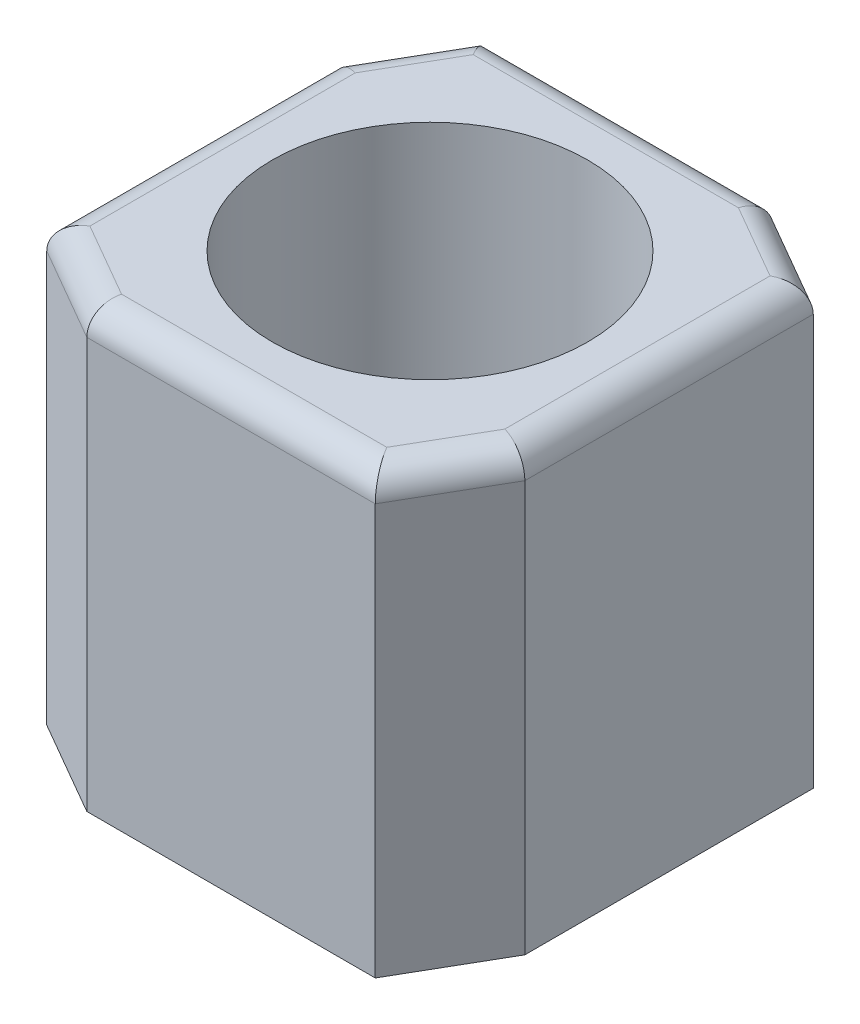
SolidWorks part; units mm, degrees
ref_plane "Front Plane" through (0, 0, 0) normal (0, 0, 1) x (1, 0, 0)
ref_plane "Top Plane" through (0, 0, 0) normal (0, 1, 0) x (1, 0, 0)
ref_plane "Right Plane" through (0, 0, 0) normal (1, 0, 0) x (0, 0, -1)
sketch "Sketch1" plane through (0, 0, 0) normal (0, 1, 0) x (1, 0, 0)
  line L1 (-3.175, -3.175) -> (3.175, -3.175)
  line L2 (-3.175, -3.175) -> (-3.175, 3.175)
  line L3 (-3.175, 3.175) -> (3.175, 3.175)
  line L4 (3.175, -3.175) -> (3.175, 3.175)
  line L5 (-3.175, -3.175) -> (3.175, 3.175) construction
  line L6 (-3.175, 3.175) -> (3.175, -3.175) construction
  circle A0 centre (0, 0) radius 2.286
  point P0 (0, 0)
  dimension "D1" = 4.572
  dimension "D2" = 6.35
  dimension "D3" = 6.35
extrude "Boss-Extrude1" add sketch "Sketch1" along normal blind 6.35
chamfer "Chamfer1" distance 0.7937 angle 60 4 edges at (-3.175, 3.175, -3.175) (3.175, 3.175, -3.175) (3.175, 3.175, 3.175) (-3.175, 3.175, 3.175)
fillet "Fillet1" radius 0.3969 8 edges at (3.175, 6.35, -0.2905) (-3.175, 6.35, 0.2905) (-2.7781, 6.35, -2.4876) (-0.2905, 6.35, -3.175) (2.4876, 6.35, -2.7781) (2.7781, 6.35, 2.4876) (0.2905, 6.35, 3.175) (-2.4876, 6.35, 2.7781)
fillet "Fillet2" radius 0.3969 1 edges at (0, 0, 2.286)
